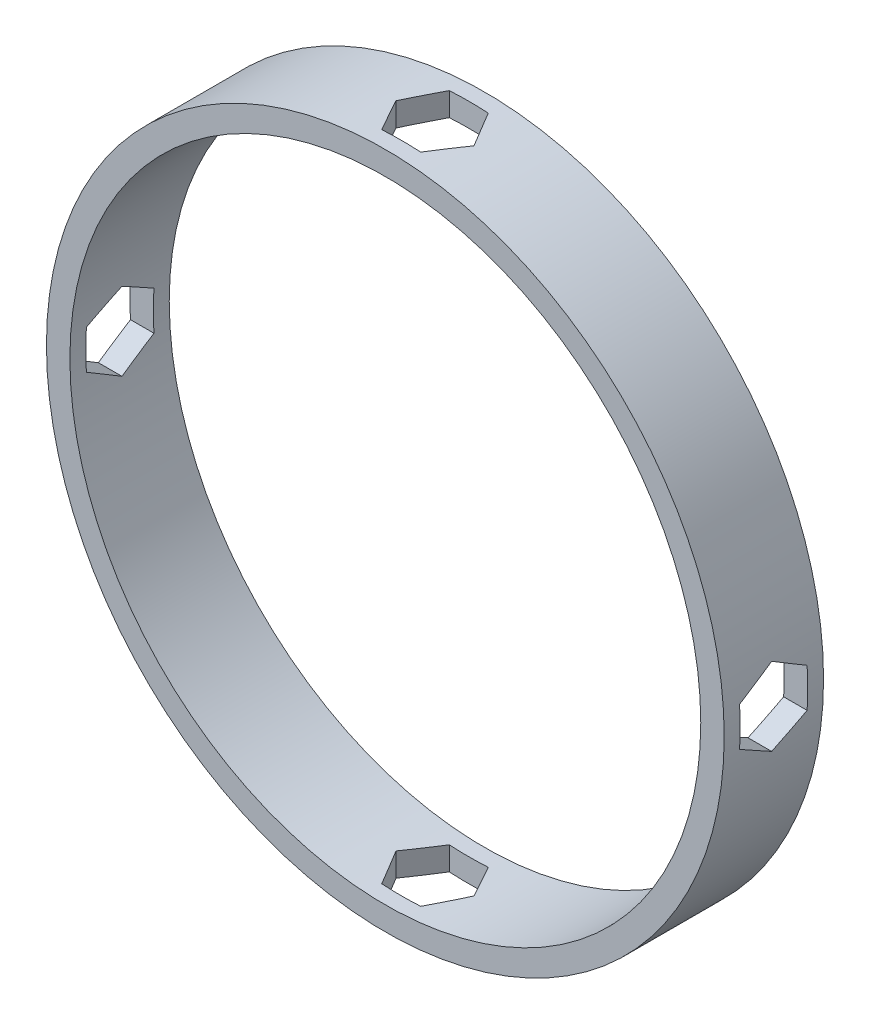
SolidWorks part; units mm, degrees
ref_plane "Front Plane" through (0, 0, 0) normal (0, 0, 1) x (1, 0, 0)
ref_plane "Top Plane" through (0, 0, 0) normal (0, 1, 0) x (1, 0, 0)
ref_plane "Right Plane" through (0, 0, 0) normal (1, 0, 0) x (0, 0, -1)
sketch "Sketch1" plane through (0, 0, 0) normal (0, 0, 1) x (1, 0, 0)
  circle A0 centre (0, 0) radius 34.11
  circle A1 centre (0, 0) radius 31.75
  dimension "D1" = 68.22
  dimension "D2" = 63.5
extrude "Boss-Extrude1" add sketch "Sketch1" along normal blind 11.5
ref_plane "Plane1" through (0, 34.11, 0) normal (0, 1, 0) x (1, 0, 0)
sketch "Sketch2" plane through (0, 34.11, 0) normal (0, 1, 0) x (1, 0, 0)
  line L0 (0, -5) -> (-3.926, -5) construction
  line L1 (3.926, -5) -> (1.963, -1.6)
  line L2 (1.963, -1.6) -> (-1.963, -1.6)
  line L3 (-1.963, -1.6) -> (-3.926, -5)
  line L4 (-3.926, -5) -> (-1.963, -8.4)
  line L5 (-1.963, -8.4) -> (1.963, -8.4)
  line L6 (1.963, -8.4) -> (3.926, -5)
  circle A1 centre (0, -5) radius 3.4 construction
  dimension "D2" = 5
  dimension "D3" = 6.8
extrude "Cut-Extrude1" cut sketch "Sketch2" against normal blind 10
pattern_circular "CirPattern2" count 4 every 90 about axis through (0, 0, 0) along (0, 0, 1) of "Cut-Extrude1"
pattern_circular "CirPattern3" [suppressed] count 2 over 360
other "Move Face1" [suppressed] parameters "D1"=1.5
pattern_circular "CirPattern4" [suppressed] count 2 every 86.64
sketch "Sketch3" plane through (0, 0, 11.5) normal (0, 0, 1) x (1, 0, 0)
  circle A1 centre (0, 0) radius 34.11
  circle A2 centre (0, 0) radius 34.11
  dimension "D1" = 0
extrude "Cut-Extrude2" cut sketch "Sketch3" against normal blind 1.5
